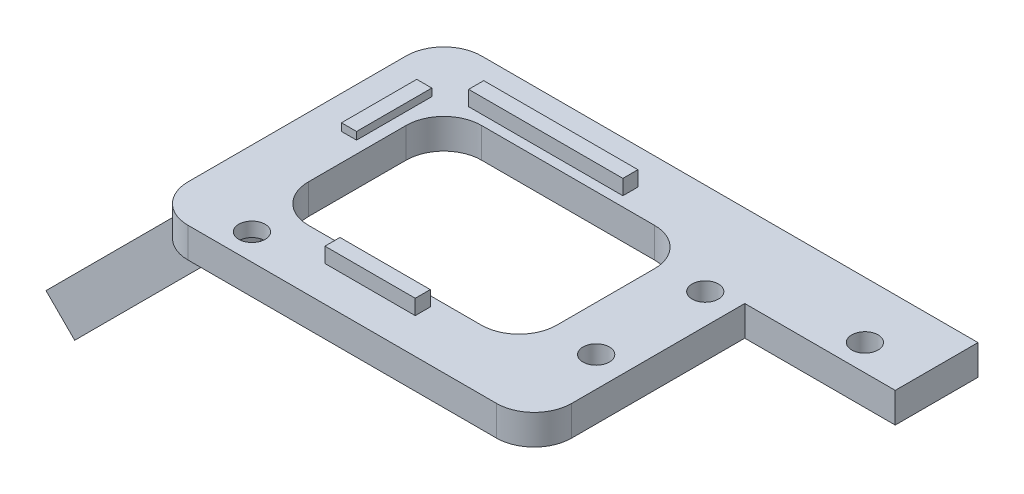
SolidWorks part; units mm, degrees
ref_plane "Front Plane" through (0, 0, 0) normal (0, 0, 1) x (1, 0, 0)
ref_plane "Top Plane" through (0, 0, 0) normal (0, 1, 0) x (1, 0, 0)
ref_plane "Right Plane" through (0, 0, 0) normal (1, 0, 0) x (0, 0, -1)
sketch "Sketch1" plane through (0, 0, 0) normal (0, 1, 0) x (1, 0, 0)
  line L0 (-16.5, 0) -> (16.5, 0) construction
  line L1 (16.5, -11.5) -> (-16.5, -11.5)
  line L2 (16.5, -11.5) -> (16.5, 11.5)
  line L3 (16.5, 11.5) -> (-16.5, 11.5)
  line L4 (-16.5, -11.5) -> (-16.5, 11.5)
  line L5 (16.5, -11.5) -> (-16.5, 11.5) construction
  line L6 (16.5, 11.5) -> (-16.5, -11.5) construction
  line L7 (26.5, -19.5) -> (-24.5, -19.5)
  line L8 (26.5, -19.5) -> (26.5, 19.5)
  line L9 (26.5, 19.5) -> (-24.5, 19.5)
  line L10 (-24.5, -19.5) -> (-24.5, 19.5)
  line L13 (0, 11.5) -> (0, -11.5) construction
  circle A0 centre (22.5, 7.25) radius 1.75
  circle A1 centre (22.5, -7.25) radius 1.75
  circle A2 centre (-14.5, -16) radius 1.75
  point P0 (0, 0)
  point P6 (0, 0)
  point P21 (-24.5, 0)
  dimension "D5" = 3.5
  dimension "D7" = 14.5
  dimension "D1" = 33
  dimension "D2" = 23
  dimension "D3" = 39
  dimension "D4" = 10
  dimension "D6" = 4
  dimension "D8" = 4.5
  dimension "D9" = 8
  dimension "D10" = 10
extrude "Boss-Extrude1" add sketch "Sketch1" along normal blind 4
fillet "Fillet1" radius 5 4 edges at (-16.5, 2, 11.5) (16.5, 2, 11.5) (16.5, 2, -11.5) (-16.5, 2, -11.5)
sketch "Sketch2" plane through (0, 4, 0) normal (0, 1, 0) x (1, 0, 0)
  line L10 (-14.5, 14.8) -> (6, 14.8)
  line L16 (-14.5, 14.8) -> (-14.5, 12.8)
  line L17 (-14.5, 12.8) -> (6, 12.8)
  line L24 (0, 11.5) -> (0, -11.5) construction
  line L25 (11.5, 11.5) -> (-11.5, 11.5) construction
  line L26 (-11.5, -11.5) -> (11.5, -11.5) construction
  line L27 (-16.5, 0) -> (16.5, 0) construction
  line L28 (-16.5, 6.5) -> (-16.5, -6.5) construction
  line L29 (16.5, -6.5) -> (16.5, 6.5) construction
  line L38 (6, 14.8) -> (6, 12.8)
  line L43 (-6, -12.8) -> (6, -12.8)
  line L44 (-6, -12.8) -> (-6, -14.8)
  line L45 (-6, -14.8) -> (6, -14.8)
  line L46 (6, -12.8) -> (6, -14.8)
  dimension "D1" = 2
  dimension "D2" = 14.5
  dimension "D3" = 12.8
  dimension "D4" = 12.8
  dimension "D5" = 6
  dimension "D6" = 12
extrude "Boss-Extrude4" add sketch "Sketch2" along normal blind 2
fillet "Fillet5" radius 5 4 edges at (-24.5, 2, 19.5) (26.5, 2, 19.5) (26.5, 2, -19.5) (-24.5, 2, -19.5)
sketch "Sketch4" plane through (0, 0, 0) normal (0, -1, 0) x (1, 0, 0)
  line L1 (-12.8546, 13.15) -> (-11.2091, 16)
  line L2 (-11.2091, 16) -> (-12.8546, 18.85)
  line L3 (-12.8546, 18.85) -> (-16.1454, 18.85)
  line L4 (-16.1454, 18.85) -> (-17.7909, 16)
  line L5 (-17.7909, 16) -> (-16.1454, 13.15)
  line L6 (-16.1454, 13.15) -> (-12.8546, 13.15)
  circle A0 centre (-14.5, 16) radius 2.85 construction
  dimension "D1" = 5.7
extrude "Cut-Extrude1" cut sketch "Sketch4" against normal blind 2.1
sketch "Sketch5" plane through (0, 4, 0) normal (0, 1, 0) x (1, 0, 0)
  line L0 (11.5, 11.5) -> (-11.5, 11.5) construction
  line L1 (-20.1, 11.5) -> (-18.1, 11.5)
  line L2 (-20.1, 11.5) -> (-20.1, 1.5)
  line L3 (-20.1, 1.5) -> (-18.1, 1.5)
  line L4 (-18.1, 11.5) -> (-18.1, 1.5)
  dimension "D1" = 10
  dimension "D2" = 2
  dimension "D3" = 18.1
extrude "Boss-Extrude5" add sketch "Sketch5" along normal blind 1
sketch "Sketch6" plane through (0, 0, 0) normal (0, 0, 1) x (1, 0, 0)
  line L3 (-50.8758, -25.4558) -> (-25.42, 0)
  line L4 (-25.42, 0) -> (-17.7909, 0)
  line L5 (-17.7909, 0) -> (-47.0613, -29.2704)
  line L7 (-50.8758, -25.4558) -> (-47.0613, -29.2704)
  line L8 (-24.5, 0) -> (-24.5, 4) construction
  dimension "D1" = 36
  dimension "D2" = 135
  dimension "D3" = 0.92
extrude "Boss-Extrude6" add sketch "Sketch6" along normal blind 7 and the other way blind 7
sketch "Sketch7" plane through (-8.8954, 8.8954, 0) normal (0.7071, -0.7071, 0) x (0, 0, -1)
  line L0 (7, -53.9747) -> (-7, -53.9747) construction
  circle A0 centre (0, -45.9747) radius 1.75
  point P4 (0, -53.9747)
  dimension "D1" = 3.5
  dimension "D2" = 8
extrude "Cut-Extrude2" cut sketch "Sketch7" against normal up to surface (5.3946 mm away) up to face at (-38.1479, -12.7279, 0)
sketch "Sketch8" plane through (-8.8954, 8.8954, 0) normal (0.7071, -0.7071, 0) x (0, 0, -1)
  line L0 (7, -12.5801) -> (33.1547, -48.7133)
  line L2 (25.0542, -54.5768) -> (7, -29.6346)
  line L3 (7, -53.9747) -> (7, -12.5801) construction
  line L4 (7, -29.6346) -> (7, -12.5801)
  line L5 (25, -45.9747) -> (20.9497, -48.9064) construction
  line L6 (25, -45.9747) -> (29.0503, -43.0429) construction
  line L8 (25.0542, -54.5768) -> (33.1547, -48.7133)
  line L9 (25, -45.9747) -> (29.1045, -51.645) construction
  circle A0 centre (25, -45.9747) radius 1.75
  circle A1 centre (0, -45.9747) radius 1.75 construction
  circle A2 centre (0, -45.9747) radius 1.75 construction
  dimension "D1" = 5
  dimension "D2" = 25
  dimension "D3" = 7
extrude "Boss-Extrude7" add sketch "Sketch8" against normal up to surface (5.3946 mm away) up to face at (-46.4564, -21.0364, 0)
sketch "Sketch10" plane through (26.5, 0, 0) normal (1, 0, 0) x (0, 0, -1)
  line L0 (-14.5, 4) -> (14.5, 4) construction
  line L1 (8.5, 4) -> (19.5, 4)
  line L2 (8.5, 4) -> (8.5, 0)
  line L3 (8.5, 0) -> (19.5, 0)
  line L4 (19.5, 4) -> (19.5, 0)
  dimension "D1" = 11
extrude "Boss-Extrude9" add sketch "Sketch10" along normal blind 20 and the other way up to surface other way up to face at (24.5178, 2, -17.5178)
sketch "Sketch11" plane through (0, 4, 0) normal (0, 1, 0) x (1, 0, 0)
  line L0 (46.5, 19.5) -> (46.5, 8.5) construction
  line L1 (46.5, 19.5) -> (-19.5, 19.5) construction
  circle A2 centre (38.97, 12) radius 1.75
  dimension "D2" = 7.53
  dimension "D1" = 3.5
  dimension "D3" = 7.5
extrude "Cut-Extrude3" cut sketch "Sketch11" against normal up to surface (4 mm away) up to face at (22.5, 0, 5.5)
ref_plane "Plane1" through (0, 0, 0) normal (-0.7071, 0.7071, 0) x (0.7071, 0.7071, 0)
ref_plane "Plane2" through (0, 0, 0) normal (0.7071, 0.7071, 0) x (0.7071, -0.7071, 0)
sketch "Sketch12" plane through (0, 0, 0) normal (0, -1, 0) x (1, 0, 0)
  line L0 (-19.5, 19.5) -> (21.5, 19.5) construction
  line L1 (16.5, 23.5) -> (36.5, 23.5)
  line L2 (16.5, 23.5) -> (16.5, 15.5)
  line L3 (16.5, 15.5) -> (36.5, 15.5)
  line L4 (36.5, 23.5) -> (36.5, 15.5)
  line L5 (26.5, 14.5) -> (26.5, -8.5) construction
  point P6 (16.5, 19.5)
  dimension "D1" = 4
  dimension "D2" = 20
  dimension "D3" = 10
extrude "Cut-Extrude4" [suppressed] cut sketch "Sketch12" against normal up to surface (4 mm away)
ref_plane "Plane3" through (10.25, 10.25, 0) normal (0.7071, 0.7071, 0) x (0.7071, -0.7071, 0)
sketch "Sketch13" plane through (10.25, 10.25, 0) normal (0.7071, 0.7071, 0) x (0.7071, -0.7071, 0)
  line L0 (8.8388, -6.5) -> (8.8388, 6.5) construction
  line L1 (8.8388, -6.5) -> (8.8388, 11.5)
  line L4 (-8.1317, -11.5) -> (8.1317, -11.5) construction
  line L5 (8.8388, -6.5) -> (8.8388, -11.5)
  line L6 (8.8388, -11.5) -> (14.8907, -11.5)
  line L7 (14.8907, -11.5) -> (14.8907, 11.5)
  line L8 (14.8907, 11.5) -> (8.8388, 11.5)
  line L9 (8.1317, 11.5) -> (-8.1317, 11.5) construction
  point P7 (0, 0)
  point P8 (0, 0)
  point P9 (8.8388, 10.724)
  point P11 (0, 0)
